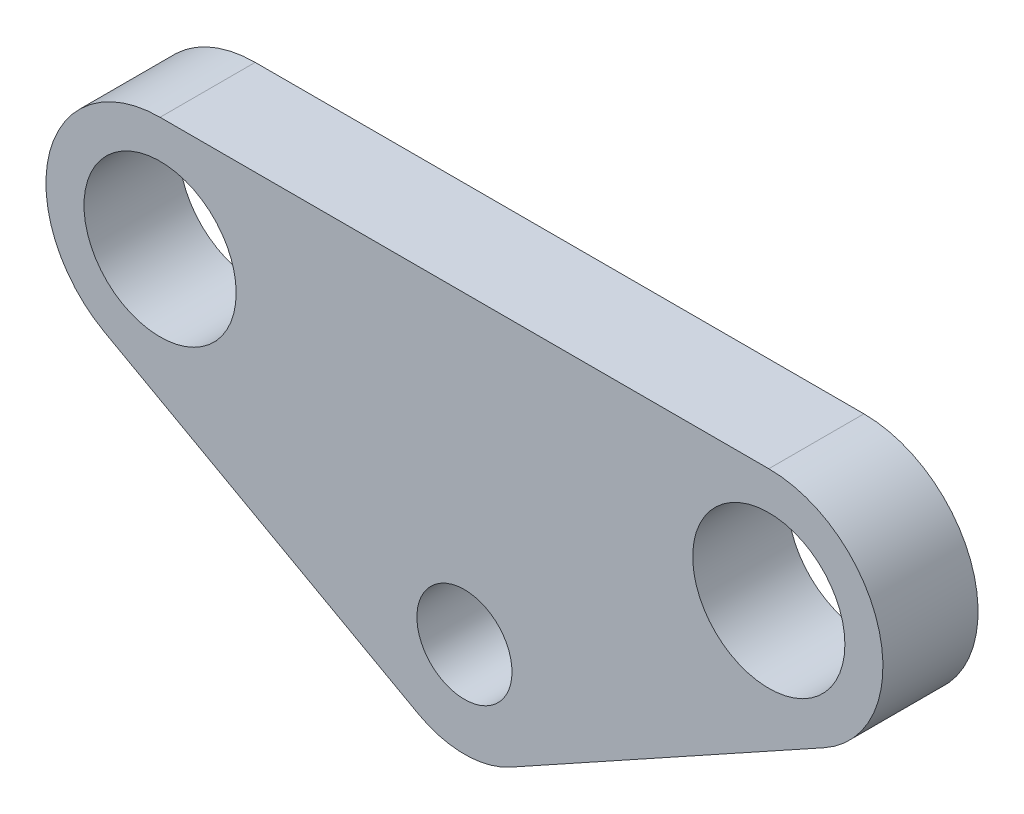
SolidWorks part; units mm, degrees
ref_plane "Front Plane" through (0, 0, 0) normal (0, 0, 1) x (1, 0, 0)
ref_plane "Top Plane" through (0, 0, 0) normal (0, 1, 0) x (1, 0, 0)
ref_plane "Right Plane" through (0, 0, 0) normal (1, 0, 0) x (0, 0, -1)
sketch "Sketch1" plane through (0, 0, 0) normal (0, 0, 1) x (1, 0, 0)
  line L0 (-16, 16) -> (16, 16)
  line L1 (0, 0) -> (0, 18.7938) construction
  line L11 (18.9059, 4.7506) -> (2.4216, -4.3745)
  line L12 (-18.9059, 4.7506) -> (-2.4216, -4.3745)
  circle A0 centre (0, 0) radius 11.5 construction
  circle A1 centre (-16, 10) radius 11.5 construction
  circle A2 centre (16, 10) radius 11.5 construction
  circle A3 centre (-16, 10) radius 4
  arc A5 (-18.9059, 4.7506) -> (-16, 16) centre (-16, 10) cw
  circle A6 centre (16, 10) radius 4
  arc A7 (18.9059, 4.7506) -> (16, 16) centre (16, 10) ccw
  circle A8 centre (0, 0) radius 2.5
  circle A9 centre (0, 0) radius 5 construction
  arc A10 (-2.4216, -4.3745) -> (2.6999, -4.2084) centre (0, 0) ccw
  point P21 (0, -12)
  dimension "D1" = 23
  dimension "D3" = 8
  dimension "D4" = 6
  dimension "D7" = 10
  dimension "D5" = 5
  dimension "D6" = 10
  dimension "D2" = 16
extrude "Boss-Extrude1" add sketch "Sketch1" along normal blind 5
